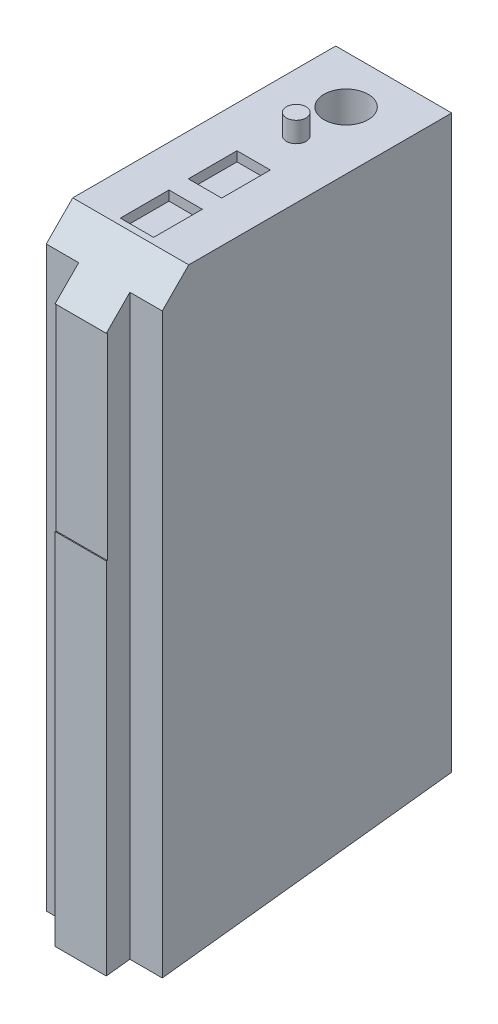
SolidWorks part; units mm, degrees
ref_plane "前视基准面" through (0, 0, 0) normal (0, 0, 1) x (1, 0, 0)
ref_plane "上视基准面" through (0, 0, 0) normal (0, 1, 0) x (1, 0, 0)
ref_plane "右视基准面" through (0, 0, 0) normal (1, 0, 0) x (0, 0, -1)
other "Configuration Table"
sketch "草图1" plane through (0, 0, 0) normal (1, 0, 0) x (0, 0, -1)
  line L0 (27.225, -59.105) -> (-37.585, -66.595)
  line L1 (-27.225, -59.105) -> (27.225, -59.105)
  line L2 (-27.225, -59.105) -> (-27.225, 59.105)
  line L3 (-27.225, 59.105) -> (27.225, 59.105)
  line L4 (27.225, -59.105) -> (27.225, 59.105)
  line L5 (-27.225, -59.105) -> (27.225, 59.105) construction
  line L6 (-27.225, 59.105) -> (27.225, -59.105) construction
  line L7 (27.225, 48.645) -> (-37.585, 48.645)
  line L8 (27.225, 48.645) -> (27.225, -66.595)
  line L9 (27.225, -66.595) -> (-37.585, -66.595)
  line L10 (-37.585, 48.645) -> (-37.585, -66.595)
  line L11 (-27.225, 59.105) -> (-37.585, 48.645)
  point P0 (0, 0)
  point P10 (-27.225, 48.645)
  dimension "D1" = 54.45
  dimension "D2" = 118.21
  dimension "D3" = 64.81
  dimension "D4" = 115.24
  dimension "D5" = 10.46
extrude "凸台-拉伸1" add sketch "草图1" along normal blind 24.02 contours L7 L4 L3 L2 | L4 L7 L2 L1 | L7 L10 L0 L1 L2 | L2 L11 L7
sketch "草图2" plane through (0, 59.105, 0) normal (0, 1, 0) x (1, 0, 0)
  line L0 (12.01, -27.225) -> (12.01, 27.225)
  line L1 (12.01, 27.225) -> (12.01, 21.935)
  line L4 (0, 27.225) -> (0, -27.225)
  line L5 (0, -27.225) -> (24.02, -27.225)
  line L6 (24.02, -27.225) -> (24.02, 27.225)
  line L7 (24.02, 27.225) -> (0, 27.225)
  line L8 (0, 27.225) -> (0, -27.225)
  line L9 (0, -27.225) -> (24.02, -27.225)
  line L10 (24.02, -27.225) -> (24.02, 27.225)
  line L11 (24.02, 27.225) -> (0, 27.225)
  circle A0 centre (12.01, 17.36) radius 4.575
  dimension "D3" = 9.15
  dimension "D2" = 5.29
  dimension "D1" = 0
extrude "切除-拉伸1" cut sketch "草图2" against normal blind 10 contours L0 A0 | L0 A0
sketch "草图3" plane through (0, 59.105, 0) normal (0, 1, 0) x (1, 0, 0)
  line L0 (12.01, 27.225) -> (12.01, -27.225)
  line L1 (12.01, 27.225) -> (12.01, 9.065)
  line L4 (0, 27.225) -> (0, -27.225)
  line L5 (0, -27.225) -> (24.02, -27.225)
  line L6 (24.02, -27.225) -> (24.02, 27.225)
  line L7 (24.02, 27.225) -> (0, 27.225)
  line L8 (0, 27.225) -> (0, -27.225)
  line L9 (0, -27.225) -> (24.02, -27.225)
  line L10 (24.02, -27.225) -> (24.02, 27.225)
  line L11 (24.02, 27.225) -> (0, 27.225)
  circle A0 centre (12.01, 17.36) radius 4.575 construction
  circle A1 centre (12.01, 17.36) radius 4.575
  circle A2 centre (12.01, 7.04) radius 2.025
  dimension "D3" = 4.05
  dimension "D2" = 18.16
  dimension "D1" = 0
extrude "凸台-拉伸2" add sketch "草图3" along normal blind 4.21 contours L0 A2 | L0 A2
sketch "草图4" plane through (0, 59.105, 0) normal (0, 1, 0) x (1, 0, 0)
  line L0 (12.01, 27.225) -> (12.01, -27.225)
  line L1 (12.01, -11.855) -> (12.01, -15.855)
  line L2 (8.56, -11.855) -> (15.46, -11.855)
  line L3 (8.56, -11.855) -> (8.56, -1.775)
  line L4 (0, 27.225) -> (0, -27.225)
  line L5 (0, -27.225) -> (24.02, -27.225)
  line L6 (24.02, -27.225) -> (24.02, 27.225)
  line L7 (24.02, 27.225) -> (0, 27.225)
  line L8 (0, 27.225) -> (0, -27.225)
  line L9 (0, -27.225) -> (24.02, -27.225)
  line L10 (24.02, -27.225) -> (24.02, 27.225)
  line L11 (24.02, 27.225) -> (0, 27.225)
  line L12 (8.56, -1.775) -> (15.46, -1.775)
  line L13 (15.46, -11.855) -> (15.46, -1.775)
  line L14 (8.56, -11.855) -> (15.46, -1.775) construction
  line L15 (8.56, -1.775) -> (15.46, -11.855) construction
  line L16 (8.56, -25.935) -> (15.46, -25.935)
  line L17 (8.56, -25.935) -> (8.56, -15.855)
  line L18 (8.56, -15.855) -> (15.46, -15.855)
  line L19 (15.46, -25.935) -> (15.46, -15.855)
  line L20 (8.56, -25.935) -> (15.46, -15.855) construction
  line L21 (8.56, -15.855) -> (15.46, -25.935) construction
  line L22 (12.01, 27.225) -> (12.01, -1.775)
  point P6 (12.01, -6.815)
  point P11 (12.01, -20.895)
  dimension "D2" = 6.9
  dimension "D3" = 6.9
  dimension "D4" = 10.08
  dimension "D5" = 10.08
  dimension "D6" = 4
  dimension "D7" = 29
  dimension "D1" = 0
extrude "切除-拉伸2" cut sketch "草图4" against normal blind 2 contours L2 L13 L12 L0 | L12 L3 L2 L0 | L18 L17 L16 L0 | L16 L19 L18 L0
sketch "草图5" plane through (0, 59.105, 0) normal (0, 1, 0) x (1, 0, 0)
  line L0 (12.01, 27.225) -> (12.01, -27.225)
  line L1 (6.71, -32.705) -> (6.71, -37.585)
  line L2 (6.71, -47.945) -> (17.31, -47.945)
  line L4 (0, 27.225) -> (0, -27.225)
  line L5 (0, -27.225) -> (24.02, -27.225)
  line L6 (24.02, -27.225) -> (24.02, 27.225)
  line L7 (24.02, 27.225) -> (0, 27.225)
  line L8 (0, 27.225) -> (0, -27.225)
  line L9 (0, -27.225) -> (24.02, -27.225)
  line L10 (24.02, -27.225) -> (24.02, 27.225)
  line L11 (24.02, 27.225) -> (0, 27.225)
  line L12 (0, -27.225) -> (0, -37.585)
  line L13 (0, -37.585) -> (24.02, -37.585)
  line L14 (24.02, -37.585) -> (24.02, -27.225)
  line L15 (24.02, -27.225) -> (0, -27.225)
  line L16 (0, -27.225) -> (0, -37.585)
  line L17 (0, -37.585) -> (24.02, -37.585)
  line L18 (24.02, -37.585) -> (24.02, -27.225)
  line L19 (24.02, -27.225) -> (0, -27.225)
  line L20 (6.71, -27.225) -> (17.31, -27.225)
  line L21 (6.71, -47.945) -> (17.31, -47.945)
  line L22 (6.71, -47.945) -> (6.71, -32.705)
  line L23 (6.71, -32.705) -> (17.31, -32.705)
  line L24 (17.31, -47.945) -> (17.31, -32.705)
  line L25 (17.31, -32.705) -> (24.02, -32.705)
  line L26 (6.71, -32.705) -> (17.31, -32.705)
  line L27 (6.71, -32.705) -> (6.71, -27.225)
  line L28 (6.71, -27.225) -> (17.31, -27.225)
  line L29 (17.31, -32.705) -> (17.31, -27.225)
  line L30 (24.02, -32.705) -> (0, -32.705)
  dimension "D3" = 10.6
  dimension "D4" = 4.88
  dimension "D1" = 0
  dimension "D2" = 0
extrude "切除-拉伸4" cut sketch "草图5" against normal through all contours L1 L30 L16 L17 | L25 L24 L17 L18
sketch "草图7" plane through (0, 0, 37.585) normal (0, 0, 1) x (1, 0, 0)
  line L0 (12.01, 59.105) -> (12.01, -66.595)
  line L1 (12.01, 59.105) -> (12.01, 39.215)
  line L2 (2.42, 15.815) -> (21.6, 15.815)
  line L3 (2.42, 15.815) -> (2.42, 39.215)
  line L4 (6.71, 48.645) -> (6.71, -66.595)
  line L5 (6.71, -66.595) -> (17.31, -66.595)
  line L6 (17.31, -66.595) -> (17.31, 48.645)
  line L7 (17.31, 48.645) -> (6.71, 48.645)
  line L8 (6.71, 48.645) -> (6.71, -66.595)
  line L9 (6.71, -66.595) -> (17.31, -66.595)
  line L10 (17.31, -66.595) -> (17.31, 48.645)
  line L11 (17.31, 48.645) -> (6.71, 48.645)
  line L12 (0, -66.031) -> (6.71, -66.031)
  line L13 (6.71, -66.031) -> (6.71, 53.5721)
  line L14 (6.71, 53.5721) -> (0, 53.5721)
  line L15 (0, 53.5721) -> (0, -66.031)
  line L16 (0, -66.031) -> (6.71, -66.031)
  line L17 (6.71, -66.031) -> (6.71, 53.5721)
  line L18 (6.71, 53.5721) -> (0, 53.5721)
  line L19 (0, 53.5721) -> (0, -66.031)
  line L20 (24.02, -66.031) -> (24.02, 53.5721)
  line L21 (24.02, 53.5721) -> (17.31, 53.5721)
  line L22 (17.31, 53.5721) -> (17.31, -66.031)
  line L23 (17.31, -66.031) -> (24.02, -66.031)
  line L24 (24.02, -66.031) -> (24.02, 53.5721)
  line L25 (24.02, 53.5721) -> (17.31, 53.5721)
  line L26 (17.31, 53.5721) -> (17.31, -66.031)
  line L27 (17.31, -66.031) -> (24.02, -66.031)
  line L28 (2.42, 39.215) -> (21.6, 39.215)
  line L29 (21.6, 15.815) -> (21.6, 39.215)
  line L30 (2.42, 15.815) -> (21.6, 39.215) construction
  line L31 (2.42, 39.215) -> (21.6, 15.815) construction
  line L32 (6.71, 53.5721) -> (6.71, 48.645)
  line L33 (6.71, 48.645) -> (17.31, 48.645)
  line L34 (17.31, 48.645) -> (17.31, 53.5721)
  line L35 (17.31, 53.5721) -> (24.02, 53.5721)
  line L36 (24.02, 53.5721) -> (24.02, 59.105)
  line L37 (24.02, 59.105) -> (0, 59.105)
  line L38 (0, 59.105) -> (0, 53.5721)
  line L39 (0, 53.5721) -> (6.71, 53.5721)
  line L40 (6.71, 53.5721) -> (6.71, 48.645)
  line L41 (6.71, 48.645) -> (17.31, 48.645)
  line L42 (17.31, 48.645) -> (17.31, 53.5721)
  line L43 (17.31, 53.5721) -> (24.02, 53.5721)
  line L44 (24.02, 53.5721) -> (24.02, 59.105)
  line L45 (24.02, 59.105) -> (0, 59.105)
  line L46 (0, 59.105) -> (0, 53.5721)
  line L47 (0, 53.5721) -> (6.71, 53.5721)
  point P18 (12.01, 27.515)
  line M25 (17.31, -66.595) -> (17.31, 48.645)
  dimension "D5" = 19.18
  dimension "D6" = 23.4
  dimension "D7" = 19.89
  dimension "D1" = 0
  dimension "D2" = 0
  dimension "D3" = 0
  dimension "D4" = 0
extrude "切除-拉伸5" cut sketch "草图7" against normal blind 0.2 contours L28 L17 L2 L0 | L28 L0 L2 M25
sketch "草图8" plane through (0, 0, 37.585) normal (0, 0, 1) x (1, 0, 0)
  line L1 (6.71, 39.215) -> (17.31, 39.215)
  line L2 (6.71, 39.215) -> (6.71, 48.635)
  line L3 (6.71, 48.635) -> (17.31, 48.635)
  line L4 (6.71, 39.215) -> (17.31, 39.215)
  line L5 (17.31, 39.215) -> (17.31, 48.645)
  line L6 (17.31, 48.645) -> (6.71, 48.645)
  line L7 (6.71, 48.645) -> (6.71, 39.215)
  line L8 (6.71, 39.215) -> (17.31, 39.215)
  line L9 (17.31, 39.215) -> (17.31, 48.645)
  line L10 (17.31, 48.645) -> (6.71, 48.645)
  line L11 (6.71, 48.645) -> (6.71, 39.215)
  line L12 (17.31, 39.215) -> (17.31, 48.635)
  line M5 (6.71, 39.215) -> (17.31, 39.215)
  line M6 (17.31, 39.215) -> (17.31, 48.645)
  line M8 (6.71, 48.645) -> (6.71, 39.215)
  dimension "D2" = 9.42
  dimension "D1" = 0
extrude "切除-拉伸6" cut sketch "草图8" against normal blind 0.2 contours L3 M8 M5 M6
sketch "草图9" plane through (0, 0, 37.585) normal (0, 0, 1) x (1, 0, 0)
  line L1 (6.71, 15.815) -> (17.31, 15.815)
  line L2 (6.71, 15.815) -> (6.71, 7.815)
  line L3 (6.71, 7.815) -> (17.31, 7.815)
  line L4 (17.31, -66.595) -> (17.31, 15.815)
  line L5 (17.31, 15.815) -> (6.71, 15.815)
  line L6 (6.71, 15.815) -> (6.71, -66.595)
  line L7 (6.71, -66.595) -> (17.31, -66.595)
  line L8 (17.31, -66.595) -> (17.31, 15.815)
  line L9 (17.31, 15.815) -> (6.71, 15.815)
  line L10 (6.71, 15.815) -> (6.71, -66.595)
  line L11 (6.71, -66.595) -> (17.31, -66.595)
  line L12 (17.31, 15.815) -> (17.31, 7.815)
  line M6 (17.31, -66.595) -> (17.31, 15.815)
  line M7 (17.31, 15.815) -> (6.71, 15.815)
  line M8 (6.71, 15.815) -> (6.71, -66.595)
  dimension "D2" = 8
  dimension "D1" = 0
extrude "切除-拉伸7" cut sketch "草图9" against normal blind 0.2 contours L3 M8 M6 M7
sketch "草图10" plane through (0, 0, 0) normal (-1, 0, 0) x (0, 0, 1)
  line L0 (21.535, 47.925) -> (21.535, 59.105)
  line L1 (14.855, 42.315) -> (21.535, 42.315)
  line L2 (14.855, 42.315) -> (14.855, 47.925)
  line L3 (14.855, 47.925) -> (21.535, 47.925)
  line L4 (21.535, 42.315) -> (21.535, 47.925)
  line L5 (-27.225, -59.105) -> (32.705, -66.031)
  line L6 (32.705, -66.031) -> (32.705, 53.5721)
  line L7 (32.705, 53.5721) -> (27.225, 59.105)
  line L8 (27.225, 59.105) -> (-27.225, 59.105)
  line L9 (-27.225, 59.105) -> (-27.225, -59.105)
  line L10 (-27.225, -59.105) -> (32.705, -66.031)
  line L11 (32.705, -66.031) -> (32.705, 53.5721)
  line L12 (32.705, 53.5721) -> (27.225, 59.105)
  line L13 (27.225, 59.105) -> (-27.225, 59.105)
  line L14 (-27.225, 59.105) -> (-27.225, -59.105)
  line L15 (14.855, 42.315) -> (21.535, 47.925) construction
  line L16 (14.855, 47.925) -> (21.535, 42.315) construction
  line L17 (14.855, 47.925) -> (-27.225, 47.925)
  point P2 (18.195, 45.12)
  dimension "D2" = 6.68
  dimension "D3" = 5.61
  dimension "D4" = 11.18
  dimension "D5" = 42.08
  dimension "D1" = 0
extrude "切除-拉伸8" cut sketch "草图10" against normal blind 2.08 contours L1 L4 L3 L2
